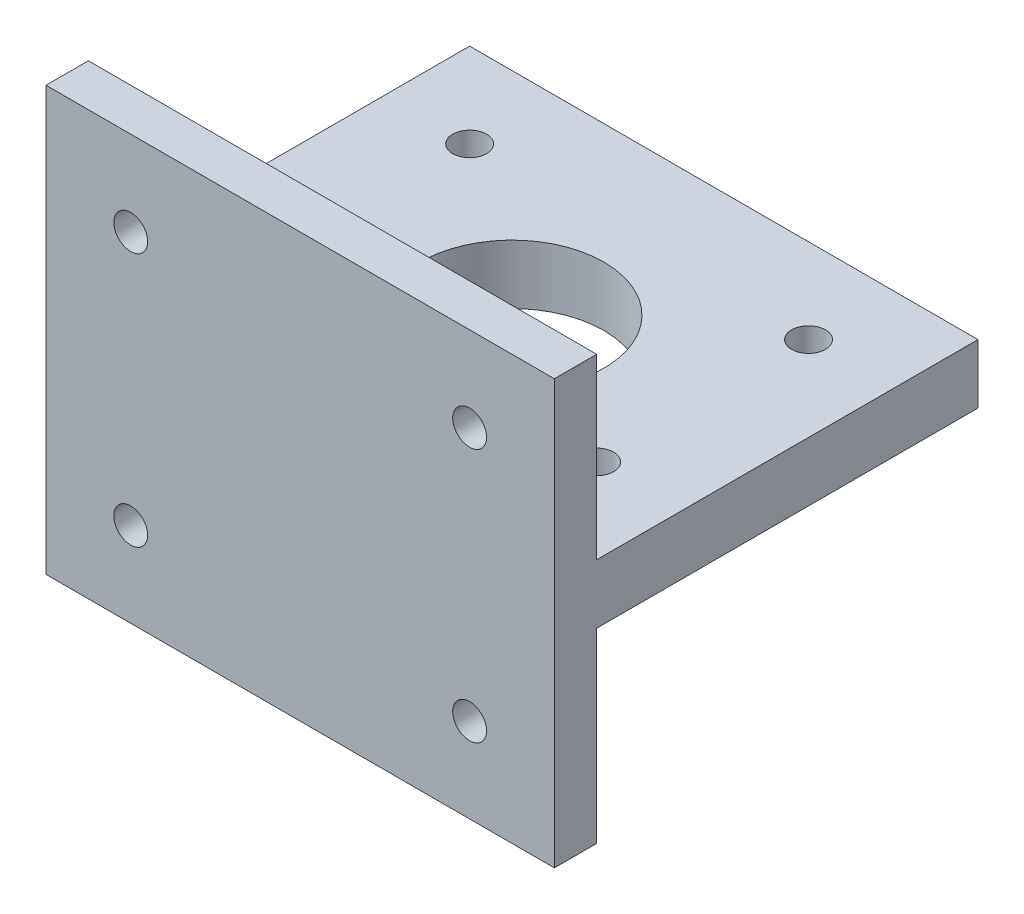
SolidWorks part; units mm, degrees
ref_plane "前视基准面" through (0, 0, 0) normal (0, 0, 1) x (1, 0, 0)
ref_plane "上视基准面" through (0, 0, 0) normal (0, 1, 0) x (1, 0, 0)
ref_plane "右视基准面" through (0, 0, 0) normal (1, 0, 0) x (0, 0, -1)
other "Configuration Table"
sketch "草图2" plane through (0, 0, 0) normal (0, 1, 0) x (1, 0, 0)
  line L1 (-30, -25) -> (30, -25)
  line L2 (-30, -25) -> (-30, 25)
  line L3 (-30, 25) -> (30, 25)
  line L4 (30, -25) -> (30, 25)
  line L5 (-30, -25) -> (30, 25) construction
  line L6 (-30, 25) -> (30, -25) construction
  circle A0 centre (0, 0) radius 10.85
  dimension "D1" = 21.7
  dimension "D2" = 50
  dimension "D3" = 60
extrude "凸台-拉伸1" add sketch "草图2" along normal blind 7
ref_plane "基准面1" through (0, 3, 0) normal (0, 1, 0) x (1, 0, 0)
sketch "草图4" plane through (0, 3, 0) normal (0, 1, 0) x (1, 0, 0)
  line L0 (30, -25) -> (30, 25) construction
  line L1 (-30, -25) -> (30, -25)
  line L2 (-30, -25) -> (-30, -20)
  line L3 (-30, -20) -> (30, -20)
  line L4 (30, -25) -> (30, -20)
  dimension "D1" = 5
extrude "凸台-拉伸2" add sketch "草图4" along normal mid plane 50
sketch "草图6" plane through (0, 0, 25) normal (0, 0, 1) x (1, 0, 0)
  line L0 (27.5, 3) -> (-27.5, 3) construction
  line L1 (-30, 28) -> (-20, 28)
  line L2 (-30, 28) -> (-30, 18)
  line L3 (-30, 18) -> (-20, 18)
  line L4 (-20, 28) -> (-20, 18)
  line L5 (0, -1000) -> (0, 49000) construction
  circle A0 centre (-20, 18) radius 2
  circle A1 centre (-20, -12) radius 2
  circle A2 centre (20, -12) radius 2
  circle A3 centre (20, 18) radius 2
  dimension "D3" = 4
  dimension "D1" = 10
  dimension "D2" = 10
extrude "切除-拉伸1" cut sketch "草图6" against normal blind 50 contours L3 A0 L4 | L4 A0 L3 | A3 | A1 | A2
sketch "草图8" plane through (0, 0, 0) normal (0, -1, 0) x (1, 0, 0)
  line L0 (0, -1000) -> (0, 49000) construction
  line L1 (-30, -25) -> (-20, -25)
  line L2 (-30, -25) -> (-30, -15)
  line L3 (-30, -15) -> (-20, -15)
  line L4 (-20, -25) -> (-20, -15)
  line L5 (-1000, 0) -> (49000, 0) construction
  line L7 (-30, 20) -> (-20, 20)
  line L8 (-30, 20) -> (-30, 10)
  line L9 (-30, 10) -> (-20, 10)
  line L10 (-20, 20) -> (-20, 10)
  circle A0 centre (-20, -15) radius 2
  circle A1 centre (20, -15) radius 2
  circle A2 centre (-20, 10) radius 2
  circle A3 centre (20, 10) radius 2
  dimension "D3" = 4
  dimension "D6" = 4
  dimension "D1" = 10
  dimension "D2" = 10
  dimension "D4" = 10
  dimension "D5" = 10
extrude "切除-拉伸4" cut sketch "草图8" against normal blind 50 contours L9 A2 L10 | L10 A2 L9 | A3 | A1 | A0
